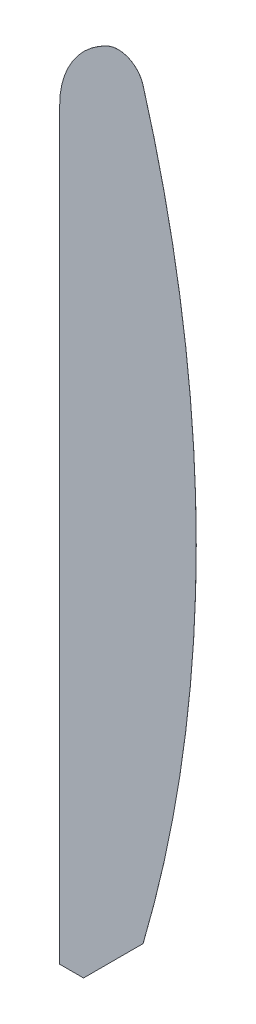
SolidWorks part; units mm, degrees
ref_plane "Front Plane" through (0, 0, 0) normal (1, 0, 0) x (0, 1, 0)
ref_plane "Top Plane" through (0, 0, 0) normal (0, 0, 1) x (0, 1, 0)
ref_plane "Right Plane" through (0, 0, 0) normal (0, 1, 0) x (-1, 0, 0)
sketch "Sketch1" plane through (0, 0, 0) normal (0, 0, 1) x (0, 1, 0)
  line L0 (0, 0) -> (0, 46433.2994) construction
  line L1 (0, 0) -> (-46433.2994, 0) construction
  line L2 (341.0561, 447.2498) -> (1519.4065, 281.6435) construction
  line L3 (0, 0) -> (156.348, 0)
  line L9 (0, 0) -> (0, -5)
  line L10 (0, -5) -> (12.5, -17.5)
  line L11 (0, 0) -> (90.5464, -28.6667)
  arc A0 (156.348, 0) -> (172, -10) centre (156.348, -17.2493) cw
  arc A1 (172, -10) -> (168.5928, -17.5) centre (167.069, -12.2838) cw
  arc A2 (12.5, -17.5) -> (168.5928, -17.5) centre (90.5464, 249.6588) ccw
  dimension "D1" = 156.348
  dimension "D2" = 5
  dimension "D3" = 28.6667
  dimension "D4" = 17.5
  dimension "Span" = 172
  dimension "D6" = 12.5
  dimension "D7" = 10
extrude "Boss-Extrude1" add sketch "Sketch1" along normal blind 0.01 contours L3 A0 A1 A2 L10 L9
equation "\"D3@Sketch1\"=\"Span@Sketch1\"/6"
equation "\"D1@Sketch1\"=\"Span@Sketch1\"*0.909"
